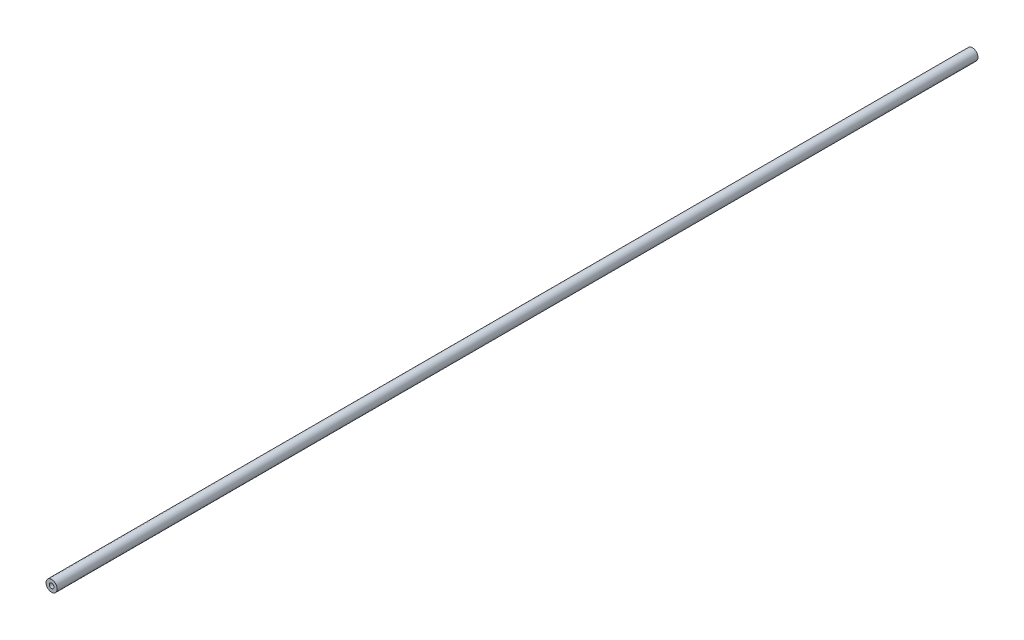
SolidWorks part; units mm, degrees
ref_plane "前视基准面" through (0, 0, 0) normal (0, 0, 1) x (1, 0, 0)
ref_plane "上视基准面" through (0, 0, 0) normal (0, 1, 0) x (1, 0, 0)
ref_plane "右视基准面" through (0, 0, 0) normal (1, 0, 0) x (0, 0, -1)
sketch "草图1" plane through (0, 0, 0) normal (0, 0, 1) x (1, 0, 0)
  circle A0 centre (0, 0) radius 6
  dimension "D1" = 12
extrude "凸台-拉伸1" add sketch "草图1" along normal mid plane 990
hole_wizard "M6 螺纹孔1" positions "草图3" profile "草图2" tap size "M6" standard "Iso"
sketch "草图3" plane through (0, 0, -495) normal (0, 0, -1) x (-1, 0, 0)
  point P0 (0, 0)
sketch "草图2" plane through (0, 0, -495) normal (1, 0, 0) x (0, 1, 0)
  line L0 (0, 0) -> (0, 16.5022)
  line L1 (0, 16.5022) -> (2.5, 15)
  line L2 (2.5, 15) -> (2.5, 0)
  line L5 (2.5, 0) -> (0, 0)
  line L10 (0, 16.5022) -> (-2.5, 15) construction
  line L11 (0, -6.35) -> (0, 107.95) construction
  dimension "螺纹孔钻头直径" = 5
  dimension "螺纹孔钻头深度" = 15
  dimension "导头角度" = 118
cosmetic thread "孔螺蚊线1"
hole_wizard "M6 螺纹孔2" positions "草图5" profile "草图6" tap size "M6" standard "ISO"
sketch "草图5" plane through (0, 0, 495) normal (0, 0, 1) x (1, 0, 0)
  point P0 (0, 0)
sketch "草图6" plane through (0, 0, 495) normal (1, 0, 0) x (0, -1, 0)
  line L0 (0, 0) -> (0, 16.5022)
  line L1 (0, 16.5022) -> (2.5, 15)
  line L2 (2.5, 15) -> (2.5, 0)
  line L5 (2.5, 0) -> (0, 0)
  line L10 (0, 16.5022) -> (-2.5, 15) construction
  line L11 (0, -6.35) -> (0, 107.95) construction
  dimension "螺纹孔钻头直径" = 5
  dimension "螺纹孔钻头深度" = 15
  dimension "导头角度" = 118
cosmetic thread "孔螺蚊线2"
